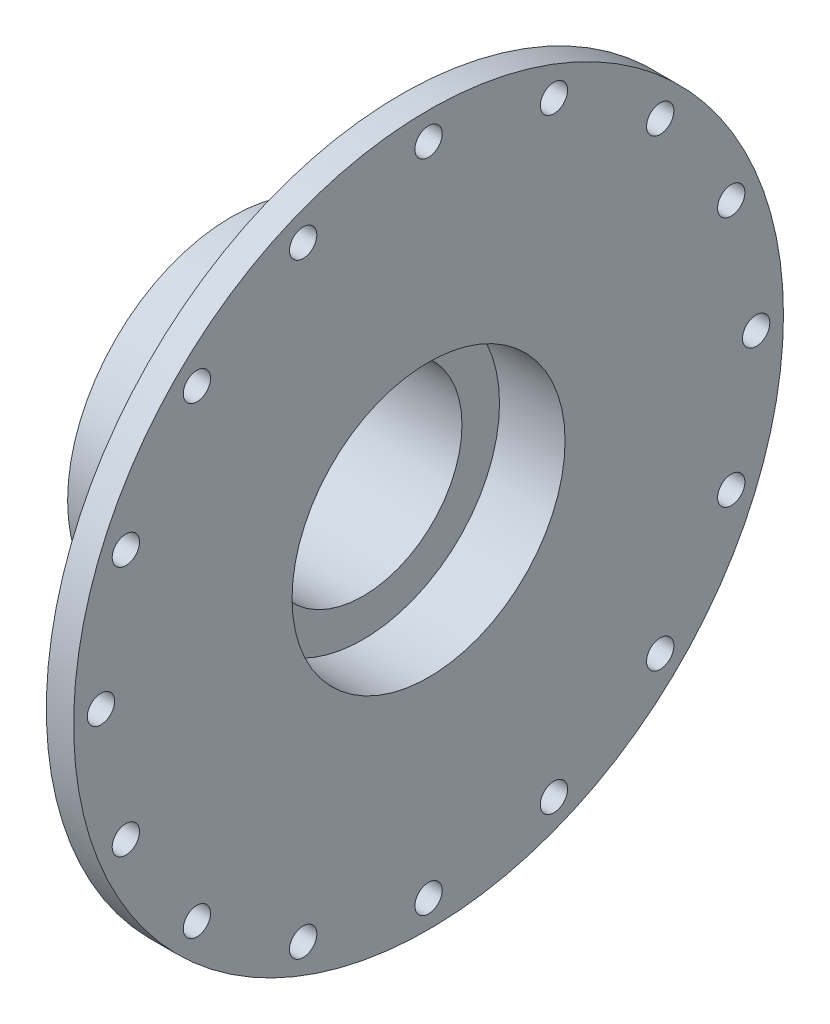
SolidWorks part; units mm, degrees
ref_plane "Front Plane" through (0, 0, 0) normal (0, 0, 1) x (1, 0, 0)
ref_plane "Top Plane" through (0, 0, 0) normal (0, 1, 0) x (1, 0, 0)
ref_plane "Right Plane" through (0, 0, 0) normal (1, 0, 0) x (0, 0, -1)
sketch "Sketch1" plane through (0, 0, 0) normal (1, 0, 0) x (0, 0, -1)
  circle A0 centre (0, 0) radius 120 construction
  circle A1 centre (0, 120) radius 5
  circle A2 centre (45.922, 110.8655) radius 5
  circle A3 centre (84.8528, 84.8528) radius 5
  circle A4 centre (110.8655, 45.922) radius 5
  circle A5 centre (120, 0) radius 5
  circle A6 centre (110.8655, -45.922) radius 5
  circle A7 centre (84.8528, -84.8528) radius 5
  circle A8 centre (45.922, -110.8655) radius 5
  circle A9 centre (0, -120) radius 5
  circle A10 centre (-45.922, -110.8655) radius 5
  circle A11 centre (-84.8528, -84.8528) radius 5
  circle A12 centre (-110.8655, -45.922) radius 5
  circle A13 centre (-120, 0) radius 5
  circle A14 centre (-110.8655, 45.922) radius 5
  circle A15 centre (-84.8528, 84.8528) radius 5
  circle A16 centre (-45.922, 110.8655) radius 5
  circle A17 centre (0, 0) radius 130
  circle A18 centre (0, 0) radius 36.2419
  point P37 (0, 0)
  dimension "D1" = 240
  dimension "D2" = 10
  dimension "D4" = 260
  dimension "D5" = 72.4838
  dimension "D3" = 16
extrude "Boss-Extrude1" add sketch "Sketch1" along normal blind 10
sketch "Sketch2" plane through (10, 0, 0) normal (1, 0, 0) x (0, 0, -1)
  circle A0 centre (0, 0) radius 36.2419
  circle A1 centre (0, 0) radius 60
  dimension "D1" = 120
extrude "Boss-Extrude2" add sketch "Sketch2" against normal blind 50
fillet "Fillet1" radius 10 1 edges at (0, 0, -60)
sketch "Sketch3" plane through (10, 0, 0) normal (1, 0, 0) x (0, 0, -1)
  circle A0 centre (0, 0) radius 50
  dimension "D1" = 100
extrude "Cut-Extrude1" cut sketch "Sketch3" against normal blind 24
sketch "Sketch4" plane through (-40, 0, 0) normal (-1, 0, 0) x (0, 0, 1)
  circle A0 centre (0, 0) radius 36.2419 construction
  circle A1 centre (0, 0) radius 60
  circle A2 centre (0, 0) radius 60
  circle A3 centre (0, 0) radius 36.2419
  dimension "D1" = 0
extrude "Boss-Extrude3" add sketch "Sketch4" along normal blind 22.2
